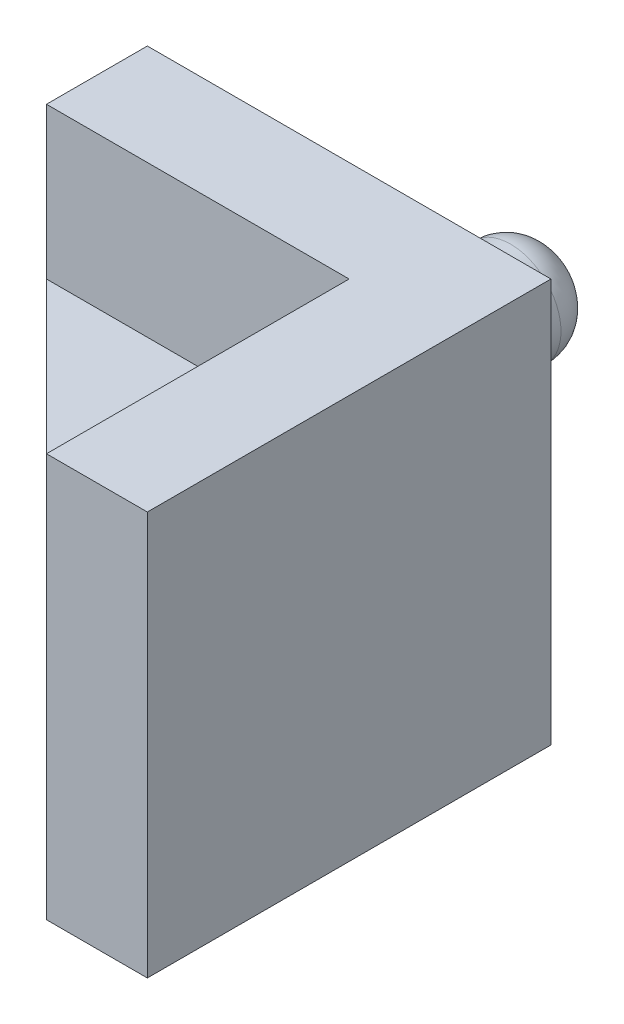
SolidWorks part; units mm, degrees
ref_plane "Front Plane" through (0, 0, 0) normal (0, 0, 1) x (1, 0, 0)
ref_plane "Top Plane" through (0, 0, 0) normal (0, 1, 0) x (1, 0, 0)
ref_plane "Right Plane" through (0, 0, 0) normal (1, 0, 0) x (0, 0, -1)
sketch "Sketch2" plane through (0, 0, 0) normal (0, 1, 0) x (1, 0, 0)
  line L1 (0, 15) -> (-15, 15)
  line L3 (5, 20) -> (-15, 20)
  line L4 (-15, 15) -> (-15, 20)
  line L6 (0, 15) -> (0, 0)
  line L7 (0, 0) -> (5, 0)
  line L8 (5, 20) -> (5, 0)
  point P2 (0, 0)
  point P7 (7.2956, 20)
  point P8 (0, 0)
  dimension "D1" = 20
  dimension "D2" = 5
  dimension "D3" = 5
  dimension "D4" = 20
extrude "Boss-Extrude1" add sketch "Sketch2" along normal mid plane 20
sketch "Sketch3" plane through (0, 0, -20) normal (0, 0, -1) x (-1, 0, 0)
  line L0 (-5, 10) -> (-5, -10) construction
  line L1 (-5, -10) -> (15, -10) construction
  circle A0 centre (5, 0) radius 2.5
  dimension "D2" = 10
  dimension "D3" = 5
  dimension "D1" = 10
extrude "Boss-Extrude2" add sketch "Sketch3" along normal blind 10
fillet "Fillet1" radius 2 1 edges at (-7.5, 0, -30)
sketch "Sketch5" plane through (0, 0, 0) normal (0, 1, 0) x (1, 0, 0)
  line L0 (-15, 15) -> (0, 0)
rib "Rib14" sketch "Sketch5" sketch "Sketch5" thickness 5 extrusion direction parallel to sketch draft on no parameters "D1"=5
